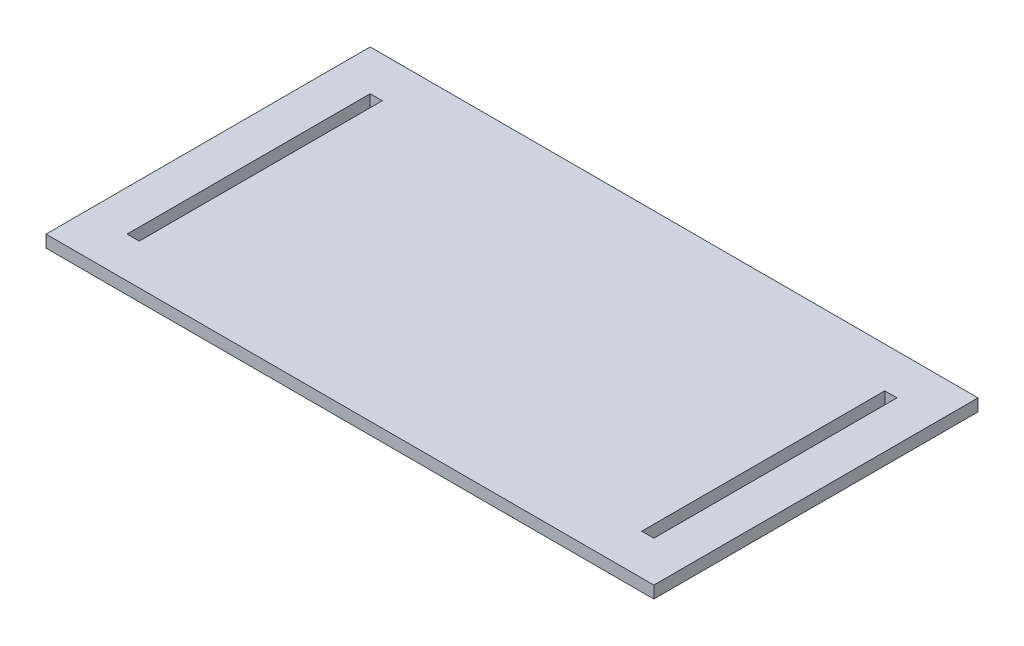
SolidWorks part; units mm, degrees
ref_plane "Front Plane" through (0, 0, 0) normal (0, 0, 1) x (1, 0, 0)
ref_plane "Top Plane" through (0, 0, 0) normal (0, 1, 0) x (1, 0, 0)
ref_plane "Right Plane" through (0, 0, 0) normal (1, 0, 0) x (0, 0, -1)
sketch "Sketch1" plane through (0, 0, 0) normal (0, 1, 0) x (1, 0, 0)
  line L1 (0, 0) -> (150, 0)
  line L2 (0, 0) -> (0, 80)
  line L3 (0, 80) -> (150, 80)
  line L4 (150, 0) -> (150, 80)
  dimension "D1" = 150
  dimension "D2" = 80
extrude "Boss-Extrude1" add sketch "Sketch1" along normal blind 3
sketch "Sketch2" plane through (0, 0, 0) normal (0, 1, 0) x (1, 0, 0)
  line L0 (75, 80) -> (75, 0)
  line L1 (10, 70) -> (13, 70)
  line L2 (10, 70) -> (10, 10)
  line L3 (10, 10) -> (13, 10)
  line L4 (13, 70) -> (13, 10)
  line L5 (150, 80) -> (0, 80) construction
  line L6 (0, 0) -> (150, 0) construction
  line L7 (140, 10) -> (137, 10)
  line L8 (140, 70) -> (137, 70)
  line L9 (140, 70) -> (140, 10)
  line L10 (137, 70) -> (137, 10)
  dimension "D1" = 10
  dimension "D2" = 3
  dimension "D3" = 10
  dimension "D4" = 10
extrude "Cut-Extrude1" cut sketch "Sketch2" along normal blind 10 contours L4 L1 L2 L3 | L8 L10 L7 L9
